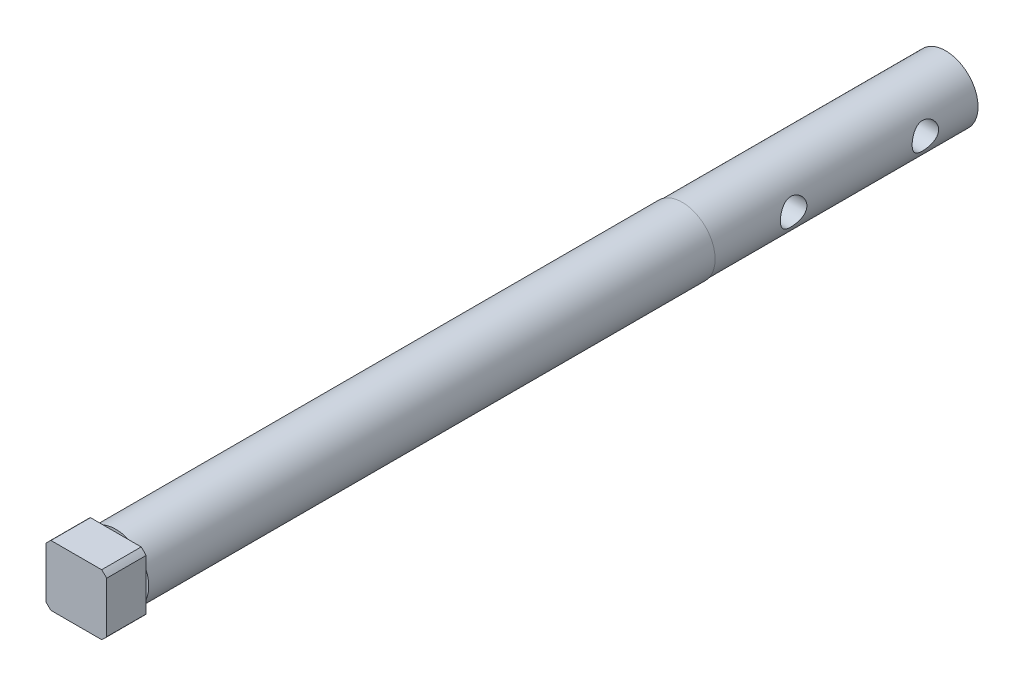
SolidWorks part; units mm, degrees
material "AISI 304"
ref_plane "Front Plane" through (0, 0, 0) normal (0, 0, 1) x (1, 0, 0)
ref_plane "Top Plane" through (0, 0, 0) normal (0, 1, 0) x (1, 0, 0)
ref_plane "Right Plane" through (0, 0, 0) normal (1, 0, 0) x (0, 0, -1)
sketch "Sketch1" plane through (0, 0, 0) normal (0, 0, 1) x (1, 0, 0)
  circle A0 centre (0, 0) radius 30
  dimension "D1" = 60
extrude "Boss-Extrude1" add sketch "Sketch1" along normal mid plane 660
sketch "Sketch2" plane through (0, 0, 0) normal (1, 0, 0) x (0, 0, -1)
  line L0 (-330, 0) -> (0, 0) construction
  line L1 (-330, 30) -> (-330, -30) construction
  line L2 (330, -30) -> (330, 30) construction
  circle A0 centre (190, 0) radius 10.05
  circle A1 centre (290, 0) radius 10.05
  dimension "D1" = 20.1
  dimension "D3" = 100
  dimension "D2" = 40
extrude "Cut-Extrude1" cut sketch "Sketch2" against normal through all both and the other way through all
ref_plane "Plane1" through (-18.5, 0, 0) normal (1, 0, 0) x (0, 0, -1)
sketch "Sketch3" plane through (-18.5, 0, 0) normal (1, 0, 0) x (0, 0, -1)
  line L0 (-330, 0) -> (-27.9799, 0) construction
  line L1 (-330, 30) -> (-330, -30) construction
  line L2 (330, -30) -> (330, 30) construction
  line L3 (-215, -7) -> (-173, -7)
  line L5 (-215, 7) -> (-173, 7)
  arc A0 (-215, 7) -> (-215, -7) centre (-215, 0) ccw
  arc A1 (-173, -7) -> (-173, 7) centre (-173, 0) ccw
  dimension "D2" = 7
  dimension "D1" = 42
  dimension "D3" = 503
extrude "Cut-Extrude2" cut sketch "Sketch3" against normal through all
pattern_linear "LPattern1" [suppressed] count 2 spacing 400
sketch "Sketch4" plane through (0, 0, 330) normal (0, 0, 1) x (1, 0, 0)
  line L17 (23, -23) -> (-23, -23)
  line L18 (23, -23) -> (23, 23)
  line L19 (23, 23) -> (-23, 23)
  line L20 (-23, -23) -> (-23, 23)
  line L21 (23, -23) -> (-23, 23) construction
  line L22 (23, 23) -> (-23, -23) construction
  point P0 (0, 0)
  dimension "D1" = 46
extrude "Cut-Extrude3" cut sketch "Sketch4" against normal blind 30 flip side to cut
sketch "Sketch5" plane through (0, 0, -330) normal (0, 0, -1) x (-1, 0, 0)
  circle A0 centre (0, 0) radius 24.61
  dimension "D1" = 49.22
extrude "Cut-Extrude4" cut sketch "Sketch5" against normal blind 200 flip side to cut
sketch "Sketch6" plane through (0, 0, -130) normal (0, 0, -1) x (-1, 0, 0)
  circle A0 centre (0, 0) radius 25
  dimension "D1" = 50
extrude "Cut-Extrude5" cut sketch "Sketch6" against normal up to surface (430 mm away) flip side to cut up to face at (0, 26.5, 300)
